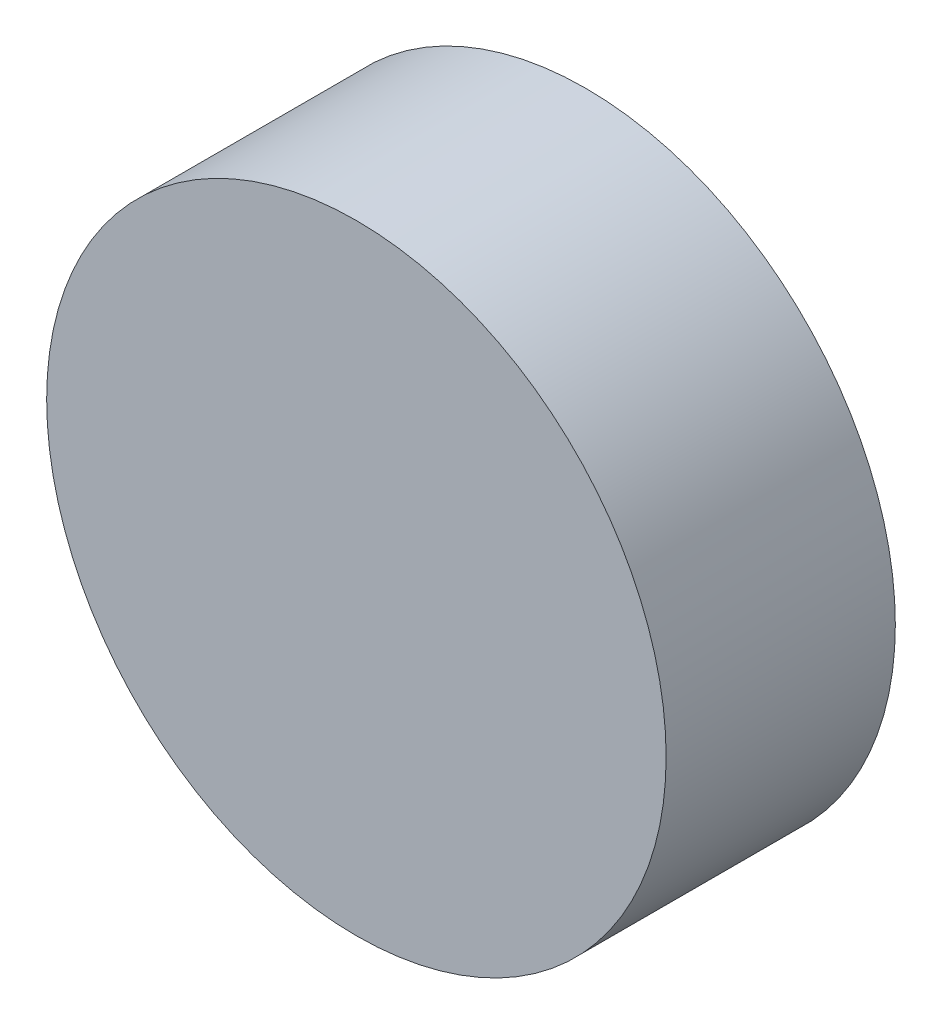
SolidWorks part; units mm, degrees
material "AISI 304"
ref_plane "Front Plane" through (0, 0, 0) normal (0, 0, 1) x (1, 0, 0)
ref_plane "Top Plane" through (0, 0, 0) normal (0, 1, 0) x (1, 0, 0)
ref_plane "Right Plane" through (0, 0, 0) normal (1, 0, 0) x (0, 0, -1)
sketch "Sketch1" plane through (0, 0, 0) normal (0, 0, 1) x (1, 0, 0)
  circle A0 centre (0, 0) radius 1.5
  dimension "D1" = 3
extrude "Boss-Extrude1" add sketch "Sketch1" along normal blind 1.11
